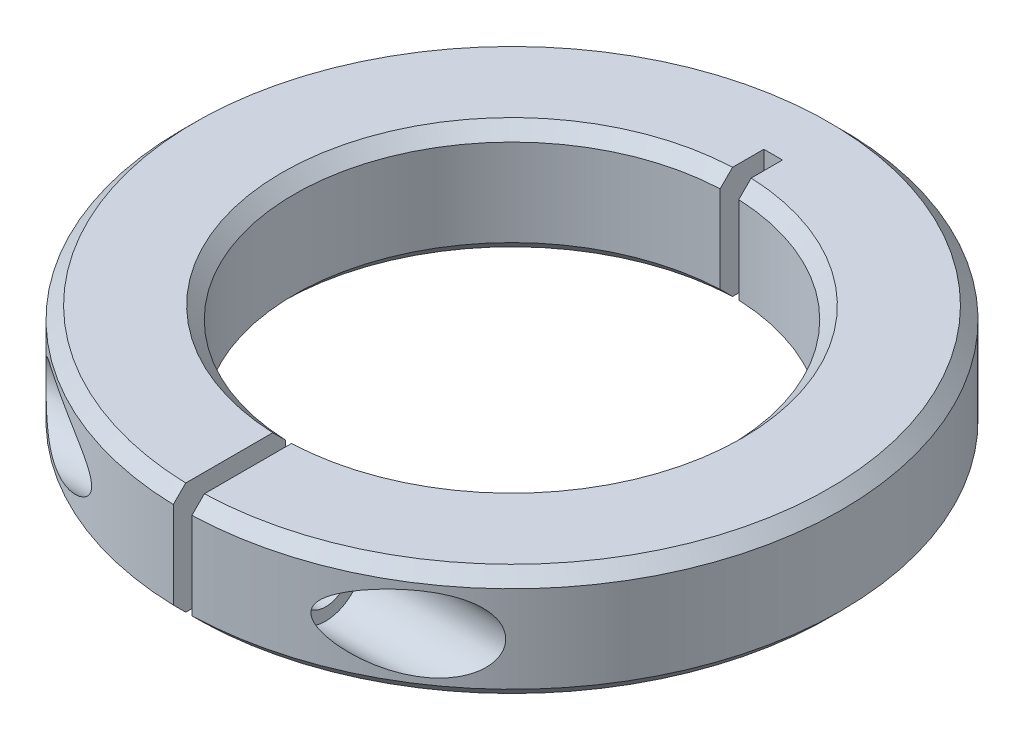
SolidWorks part; units mm, degrees
ref_plane "Front Plane" through (0, 0, 0) normal (0, 0, 1) x (1, 0, 0)
ref_plane "Top Plane" through (0, 0, 0) normal (0, 1, 0) x (1, 0, 0)
ref_plane "Right Plane" through (0, 0, 0) normal (1, 0, 0) x (0, 0, -1)
sketch "Sketch1" plane through (0, 0, 0) normal (0, 1, 0) x (1, 0, 0)
  line L0 (0, 0) -> (0, 21) construction
  line L1 (-0.75, 21) -> (0.75, 21)
  line L2 (0.75, 21) -> (0.75, 17.4839)
  line L3 (-0.75, 21) -> (-0.75, 17.4839)
  line L4 (0.75, -17.4839) -> (0.75, -26.4894)
  line L5 (-0.75, -17.4839) -> (-0.75, -26.4894)
  line L6 (-6.5622, -22.6971) -> (7.4378, -22.6971) construction
  arc A0 (-0.75, 17.4839) -> (-0.75, -17.4839) centre (0, 0) ccw
  arc A1 (0.75, -26.4894) -> (-0.75, -26.4894) centre (0, 0) ccw
  circle A2 centre (0, 0) radius 17.5 construction
  arc A3 (0.75, -17.4839) -> (0.75, 17.4839) centre (0, 0) ccw
  circle A4 centre (0, 0) radius 26.5 construction
  point P9 (0, 21)
  point P18 (0.4378, -22.6971)
  dimension "D1" = 35
  dimension "D3" = 21
  dimension "D4" = 1.5
  dimension "D2" = 9
extrude "Boss-Extrude1" add sketch "Sketch1" along normal mid plane 9
chamfer "Chamfer2" distance 1 angle 45 3 edges at (0, 4.5, -26.5) (17.5, 4.5, 0) (-17.5, 4.5, 0)
chamfer "Chamfer3" distance 1 angle 45 3 edges at (-17.5, -4.5, 0) (17.5, -4.5, 0) (0, -4.5, -26.5)
sketch "Sketch2" plane through (0, 0, 0) normal (1, 0, 0) x (0, 0, -1)
  line L0 (-25.489, -4.5) -> (25.5, -4.5) construction
  line L1 (-26.4894, 3.5) -> (-26.4894, -3.5) construction
  circle A0 centre (-21.9898, 0) radius 2
  circle A1 centre (-21.9898, 0) radius 3
  point P3 (0, 0)
  point P6 (-20.8254, 0)
  point P7 (-21.9898, 0)
  dimension "D1" = 4.5
  dimension "D2" = 4
  dimension "D3" = 6
  dimension "D4" = 4.4996
extrude "Cut-Extrude1" cut sketch "Sketch2" against normal through all both and the other way through all contours A0
ref_plane "Plane1" through (20, 0, 0) normal (1, 0, 0) x (0, 0, -1)
sketch "Sketch3" plane through (20, 0, 0) normal (1, 0, 0) x (0, 0, -1)
  circle A0 centre (-21.9898, 0) radius 3
  dimension "D1" = 6
extrude "Cut-Extrude4" cut sketch "Sketch3" against normal blind 13
mirror "Mirror3" about plane through (0, 0, 0) normal (1, 0, 0) of "Cut-Extrude4"
